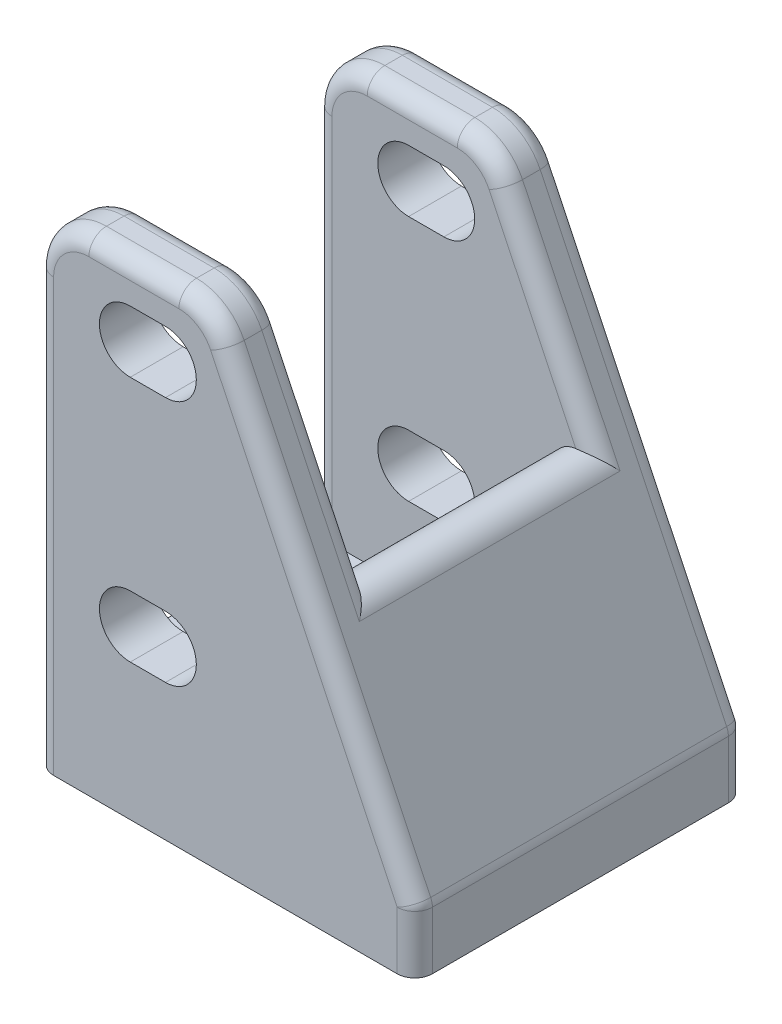
SolidWorks part; units mm, degrees
ref_plane "Front Plane" through (0, 0, 0) normal (0, 0, 1) x (1, 0, 0)
ref_plane "Top Plane" through (0, 0, 0) normal (0, 1, 0) x (1, 0, 0)
ref_plane "Right Plane" through (0, 0, 0) normal (1, 0, 0) x (0, 0, -1)
sketch "Sketch1" plane through (0, 0, 0) normal (0, 1, 0) x (1, 0, 0)
  line L1 (-21.5, -12.8) -> (21.5, -12.8)
  line L2 (-21.5, -12.8) -> (-21.5, 12.8)
  line L3 (-21.5, 12.8) -> (21.5, 12.8)
  line L4 (21.5, -12.8) -> (21.5, 12.8)
  line L5 (-21.5, -12.8) -> (21.5, 12.8) construction
  line L6 (-21.5, 12.8) -> (21.5, -12.8) construction
  circle A0 centre (-8.8, 0) radius 3.2305 construction
  circle A1 centre (11.2, 0) radius 3.2305 construction
  point P0 (0, 0)
  point P10 (0, 0)
  point P11 (14.0577, 0)
  dimension "D3" = 6.461
  dimension "D1" = 43
  dimension "D2" = 25.6
  dimension "D4" = 12.7
  dimension "D5" = 20
extrude "Boss-Extrude1" add sketch "Sketch1" along normal blind 7
sketch "Sketch2" plane through (0, 0, 12.8) normal (0, 0, 1) x (1, 0, 0)
  line L0 (21.5, 7) -> (21.5, 0) construction
  line L1 (-21.5, 0) -> (21.5, 0) construction
  line L2 (-21.5, 7) -> (-21.5, 0) construction
  line L3 (21.5, 7) -> (21.5, 0)
  line L4 (-21.5, 0) -> (21.5, 0)
  line L5 (-21.5, 7) -> (-21.5, 0)
  line L6 (-21.5, 7) -> (-21.5, 55)
  line L7 (-21.5, 55) -> (-1.5, 55)
  line L8 (-1.5, 55) -> (21.5, 7)
  line L9 (-21.5, 7) -> (21.5, 7) construction
  line L10 (-10.8, 47) -> (-6.8, 47) construction
  line L11 (-10.8, 50.5) -> (-6.8, 50.5)
  line L12 (-10.8, 43.5) -> (-6.8, 43.5)
  line L13 (-10.8, 19) -> (-6.8, 19) construction
  line L14 (-10.8, 22.5) -> (-6.8, 22.5)
  line L15 (-10.8, 15.5) -> (-6.8, 15.5)
  circle A0 centre (-8.8, 47) radius 3.5 construction
  circle A1 centre (-8.8, 19) radius 3.5 construction
  arc A2 (-10.8, 50.5) -> (-10.8, 43.5) centre (-10.8, 47) ccw
  arc A3 (-6.8, 43.5) -> (-6.8, 50.5) centre (-6.8, 47) ccw
  arc A4 (-10.8, 22.5) -> (-10.8, 15.5) centre (-10.8, 19) ccw
  arc A5 (-6.8, 15.5) -> (-6.8, 22.5) centre (-6.8, 19) ccw
  point P13 (-8.8, 47)
  point P20 (-8.8, 19)
  dimension "D1" = 7
  dimension "D2" = 12.7
  dimension "D3" = 20
  dimension "D4" = 12
  dimension "D5" = 8
  dimension "D6" = 55
  dimension "D7" = 4
extrude "Boss-Extrude2" add sketch "Sketch2" along normal blind 6
mirror "Mirror1" about plane through (0, 0, 0) normal (0, 0, 1) of "Boss-Extrude2"
fillet "Fillet1" radius 6 4 edges at (-1.5, 55, -15.8) (-21.5, 55, -15.8) (-21.5, 55, 15.8) (-1.5, 55, 15.8)
sketch "Sketch3" plane through (0, 7, 0) normal (0, 1, 0) x (1, 0, 0)
  line L0 (21.5, -12.8) -> (0.1327, -12.8) construction
  line L1 (21.5, 12.8) -> (5.5, 12.8)
  line L2 (21.5, 12.8) -> (21.5, -12.8)
  line L3 (21.5, -12.8) -> (5.5, -12.8)
  line L4 (5.5, 12.8) -> (5.5, -12.8)
  line L5 (-21.5, 12.8) -> (-21.5, -12.8) construction
  dimension "D1" = 27
extrude "Boss-Extrude3" add sketch "Sketch3" along normal up to surface up to face at (10.8163, 29.2964, -15.8)
fillet "Fillet2" radius 3 1 edges at (5.5, 40.3913, 0)
fillet "Fillet3" radius 2 23 edges at (-21.5, 28, 12.8) (-19.7426, 53.2426, 12.8) (-10.3891, 55, 12.8) (-2.0811, 54.0772, 12.8) (-21.5, 28, -12.8) (-19.7426, 53.2426, -12.8) (-10.3891, 55, -12.8) (-2.0811, 54.0772, -12.8) (5.6691, 40.0385, 12.8) (5.6691, 40.0385, -12.8) (-21.5, 24.5, -18.8) (-19.7426, 53.2426, -18.8) (-10.3891, 55, -18.8) (-2.0811, 54.0772, -18.8) (-21.5, 24.5, 18.8) (-19.7426, 53.2426, 18.8) (-10.3891, 55, 18.8) (-2.0811, 54.0772, 18.8) (10.8163, 29.2964, -18.8) (10.8163, 29.2964, 18.8) (21.5, 7, 0) (21.5, 3.5, 18.8) (21.5, 3.5, -18.8)
